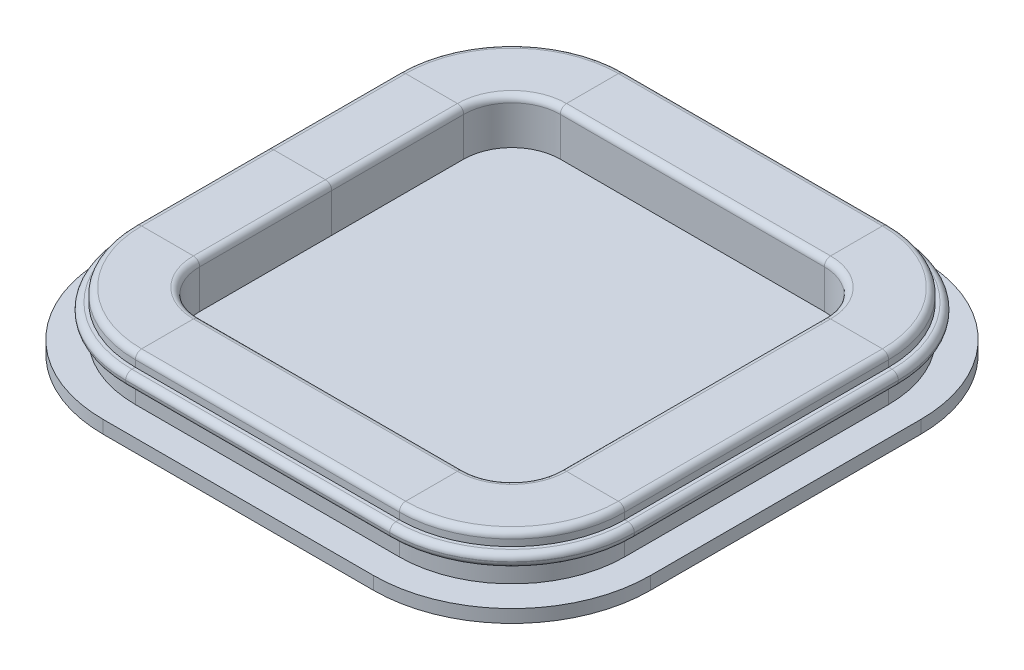
SolidWorks part; units mm, degrees
ref_plane "Front Plane" through (0, 0, 0) normal (0, 0, 1) x (1, 0, 0)
ref_plane "Top Plane" through (0, 0, 0) normal (0, 1, 0) x (1, 0, 0)
ref_plane "Right Plane" through (0, 0, 0) normal (1, 0, 0) x (0, 0, -1)
sketch "Sketch2" plane through (0, 0, 0) normal (0, 1, 0) x (1, 0, 0)
  line L1 (-10.5, -21.25) -> (10.5, -21.25)
  line L2 (-21.25, -10.5) -> (-21.25, 10.5)
  line L3 (-10.5, 21.25) -> (10.5, 21.25)
  line L4 (21.25, -10.5) -> (21.25, 10.5)
  line L5 (-21.25, -21.25) -> (21.25, 21.25) construction
  line L6 (-21.25, 21.25) -> (21.25, -21.25) construction
  arc A0 (-10.5, -21.25) -> (-21.25, -10.5) centre (-10.5, -10.5) cw
  arc A1 (10.5, -21.25) -> (21.25, -10.5) centre (10.5, -10.5) ccw
  arc A2 (10.5, 21.25) -> (21.25, 10.5) centre (10.5, 10.5) cw
  arc A3 (-21.25, 10.5) -> (-10.5, 21.25) centre (-10.5, 10.5) cw
  point P0 (0, 0)
  dimension "D3" = 10.75
  dimension "D1" = 42.5
  dimension "D2" = 42.5
extrude "Boss-Extrude1" add sketch "Sketch2" along normal blind 1
sketch "Sketch3" plane through (0, 1, 0) normal (0, 1, 0) x (1, 0, 0)
  line L1 (10.25, 19) -> (-10.25, 19)
  line L2 (19, 10.25) -> (19, -10.25)
  line L3 (10.25, -19) -> (-10.25, -19)
  line L4 (-19, 10.25) -> (-19, -10.25)
  line L5 (19, 19) -> (-19, -19) construction
  line L6 (19, -19) -> (-19, 19) construction
  arc A0 (10.25, 19) -> (19, 10.25) centre (10.25, 10.25) cw
  arc A1 (-10.25, 19) -> (-19, 10.25) centre (-10.25, 10.25) ccw
  arc A2 (-10.25, -19) -> (-19, -10.25) centre (-10.25, -10.25) cw
  arc A3 (19, -10.25) -> (10.25, -19) centre (10.25, -10.25) cw
  point P0 (0, 0)
  dimension "D3" = 8.75
  dimension "D1" = 38
  dimension "D2" = 38
sketch "Sketch11" plane through (0, 0, 0) normal (0, 0, 1) x (1, 0, 0)
  line L0 (-14, 1) -> (-19, 1)
  line L1 (-19, 1) -> (-19, 2.5)
  line L2 (-19, 2.5) -> (-19.26, 2.5)
  line L3 (-19.75, 2.99) -> (-19.75, 3.01)
  line L4 (-19.26, 3.5) -> (-19, 3.5)
  line L5 (-19, 3.5) -> (-19, 4.01)
  line L6 (-18.51, 4.5) -> (-14.49, 4.5)
  line L7 (-14, 4.01) -> (-14, 1)
  line L9 (-10.25, 1) -> (-19, 1) construction
  arc A0 (-14.49, 4.5) -> (-14, 4.01) centre (-14.49, 4.01) cw
  arc A1 (-19, 4.01) -> (-18.51, 4.5) centre (-18.51, 4.01) cw
  arc A2 (-19.26, 2.5) -> (-19.75, 2.99) centre (-19.26, 2.99) cw
  arc A3 (-19.75, 3.01) -> (-19.26, 3.5) centre (-19.26, 3.01) cw
  point P15 (-19, 4.5)
  point P18 (-19.75, 2.5)
  point P21 (-19.75, 3.5)
  dimension "D8" = 0.49
  dimension "D1" = 3.5
  dimension "D2" = 1.5
  dimension "D3" = 0.75
  dimension "D4" = 1
  dimension "D5" = 1
  dimension "D6" = 19
  dimension "D7" = 5
sweep "Sweep3" add profiles "Sketch11" path "Sketch3"
